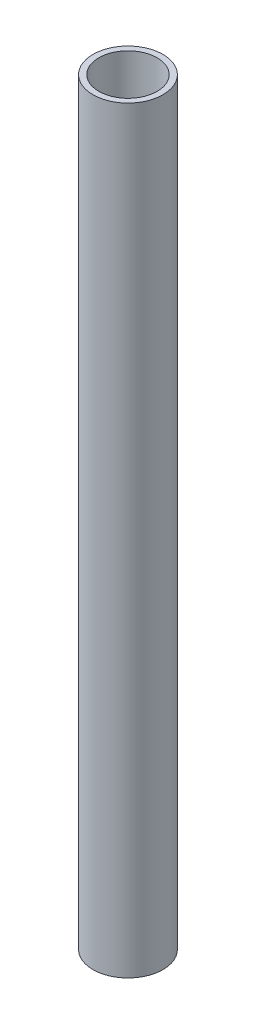
SolidWorks part; units mm, degrees
material "Thornel Mat VMA"
ref_plane "前视基准面" through (0, 0, 0) normal (0, 0, 1) x (1, 0, 0)
ref_plane "上视基准面" through (0, 0, 0) normal (0, 1, 0) x (1, 0, 0)
ref_plane "右视基准面" through (0, 0, 0) normal (1, 0, 0) x (0, 0, -1)
sketch "草图1" plane through (0, 0, 0) normal (0, 1, 0) x (1, 0, 0)
  circle A1 centre (0, 0) radius 6
  dimension "D1" = 12
extrude "拉伸-薄壁1" add sketch "草图1" along normal blind 130 thin thin type one direction reverse wall 1
sketch "草图2" plane through (0, 0, 0) normal (0, 0, 1) x (1, 0, 0)
  line L0 (-6, 0) -> (6, 0) construction
  circle A0 centre (0, 17) radius 2
  dimension "D1" = 4
  dimension "D2" = 17
extrude "切除-拉伸1" [suppressed] cut sketch "草图2" against normal through all both and the other way through all
